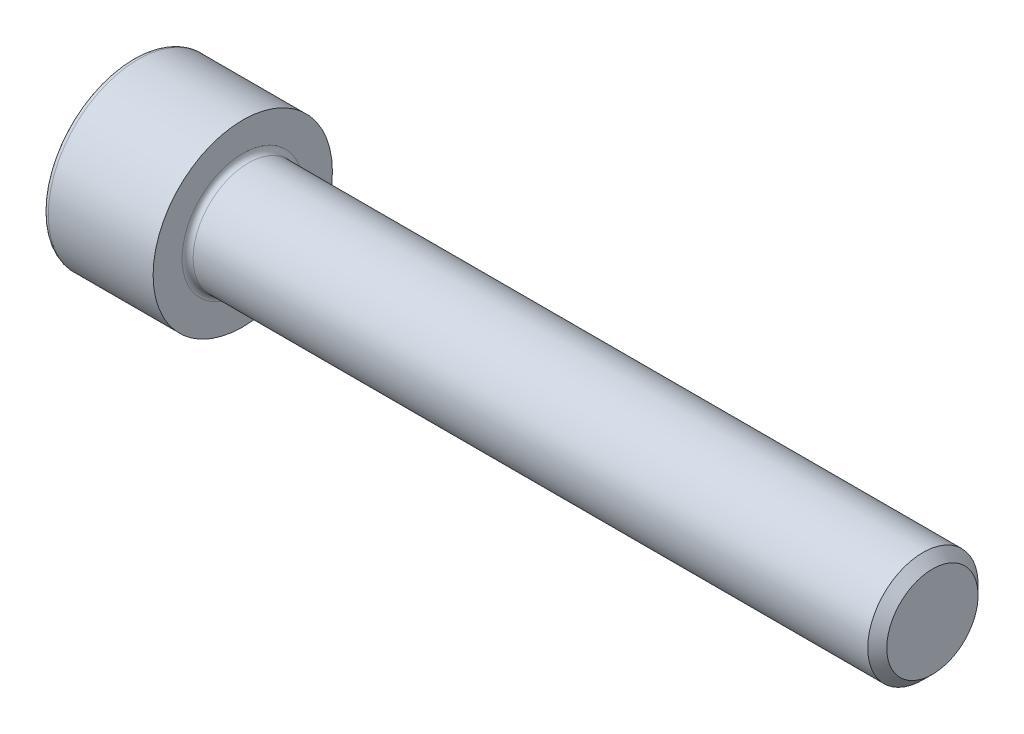
SolidWorks part; units mm, degrees
revolve "Base-Revolve" add sketch "BodySke"
sketch "BodySke" plane through (0, 0, 0) normal (0, 0, 1) x (1, 0, 0)
  line L0 (0, 0) -> (0, 6.5)
  line L1 (0, 6.5) -> (8, 6.5)
  line L2 (8, 6.5) -> (8, 4)
  line L3 (8, 4) -> (57.3095, 4)
  line L4 (58, 3.3095) -> (58, 0)
  line L5 (58, 0) -> (0, 0)
  line L6 (-31.75, 0) -> (127, 0) construction
  line L8 (58, 3.3095) -> (57.3095, 4)
  line L10 (58, -3.3095) -> (57.3095, -4) construction
  line L11 (9.25, 9.525) -> (9.25, 3.175) construction
  line L12 (30, 9.525) -> (30, 3.175) construction
  line L13 (-2, 9.525) -> (-2, 3.175) construction
  dimension "Head_ht" = 8
  dimension "Length" = 50
  dimension "Body_ch_ang" = 45
  dimension "Diameter" = 8
  dimension "Minor_dia" = 6.619
  dimension "Advance" = 1.25
  dimension "Thread_nom" = 28
  dimension "Thread_length" = 60
  dimension "Head_dia" = 13
cosmetic thread "ThreadCosmetic" [suppressed]
fillet "Fillet1" radius 0.4 1 edges at (8, 0, 4)
fillet "Fillet2" radius 0.4 1 edges at (0, 0, 6.5)
ref_plane "Plane1" through (0, 0, 0) normal (0, 0, 1) x (1, 0, 0)
ref_plane "Plane2" through (0, 0, 0) normal (0, 1, 0) x (1, 0, 0)
ref_plane "Plane3" through (0, 0, 0) normal (1, 0, 0) x (0, 0, -1)
sketch "Sketch2" plane through (0, 0, 0) normal (0, 0, 1) x (1, 0, 0)
  line L0 (0, 3.0475) -> (4, 3.0475)
  line L1 (4, 3.0475) -> (5.7595, 0)
  line L2 (-31.75, 0) -> (127, 0) construction
  line L3 (5.7595, 0) -> (0, 0)
  line L4 (0, 0) -> (0, 3.0475)
  line L6 (0, 0) -> (47.625, 0) construction
  dimension "D1" = 3.0475
  dimension "D2" = 60
  dimension "Depth" = 4
revolve "Hex-PreBroach" cut sketch "Sketch2" angle 360 about L6
sketch "Sketch3" plane through (0, 0, 0) normal (-1, 0, 0) x (0, 0.5, 0.866)
  line L0 (1.7595, 3.0475) -> (-1.7595, 3.0475)
  line L1 (-1.7595, 3.0475) -> (-3.5189, 0)
  line L2 (1.7595, 3.0475) -> (3.5189, 0)
  line L3 (1.7595, -3.0475) -> (3.5189, 0)
  line L4 (1.7595, -3.0475) -> (-1.7595, -3.0475)
  line L5 (-1.7595, -3.0475) -> (-3.5189, 0)
  dimension "D1" = 3.0475
  dimension "D2" = 3.0475
  dimension "Hex_size" = 6.095
extrude "Hex" cut sketch "Sketch3" against normal blind 4
sketch "ThdSchSke" plane through (0, 0, 0) normal (0, 0, 1) x (1, 0, 0)
  line L0 (30, -3.3095) -> (29.5165, -4)
  line L1 (30, -3.3095) -> (30.4835, -4)
  line L2 (30.4835, -4) -> (30.4835, -5)
  line L3 (-3.175, 0) -> (5.1513, 0) construction
  line L4 (0, 6.1) -> (0, -6.1) construction
  line L5 (30.4835, -5) -> (29.5165, -5)
  line L6 (29.5165, -5) -> (29.5165, -4)
  dimension "Thread_minor" = 6.619
  dimension "Diameter" = 8
  dimension "Start" = 30
revolve "ThreadSchematic" [suppressed] cut sketch "ThdSchSke" angle 360 about L3
pattern_linear "ThdSchPat" [suppressed]
equation "\"D2@Sketch3\" = \"Hex_size@Sketch3\" / 2"
equation "\"D1@Sketch3\" = \"Hex_size@Sketch3\" / 2"
equation "\"D1@Sketch2\" = \"Hex_size@Sketch3\" / 2"
equation "\"Thread_minor@ThreadCosmetic\"  =  \"Minor_dia@BodySke\""
equation "\"Depth@Sketch2\" =  \"Key_eng@Hex\""
equation "\"Thread_length@ThreadCosmetic\" = ((sgn( (\"Length@BodySke\" - \"Advance@BodySke\" * 3.0) - \"Thread_nom@BodySke\" )-1)*( (\"Length@BodySke\" - \"Advance@BodySke\" * 3.0) - \"Thread_nom@BodySke\" ))/-2+ \"Thread_nom@BodySke\""
equation "\"Thread_minor@ThdSchSke\" = \"Minor_dia@BodySke\""
equation "\"Diameter@ThdSchSke\" = \"Diameter@BodySke\""
equation "\"Overcut@ThdSchSke\" = \"Diameter@BodySke\" * 1.25"
equation "\"Start@ThdSchSke\" = \"Head_ht@BodySke\" + \"Length@BodySke\" - \"Thread_length@ThreadCosmetic\"  '---Non-countersunk---"
equation "\"Num_threads@ThdSchPat\" = int( \"Thread_length@ThreadCosmetic\" / \"Advance@BodySke\" + 0.999 )  + 1"
equation "\"Advance@ThdSchPat\" = \"Thread_length@ThreadCosmetic\" /  (\"Num_threads@ThdSchPat\" - 1) 'relax it"
equation "\"Num_threads@ThdSchPat\" = \"Num_threads@ThdSchPat\" - sgn( \"Num_threads@ThdSchPat\" - 1) '---chamfered tips only---"
